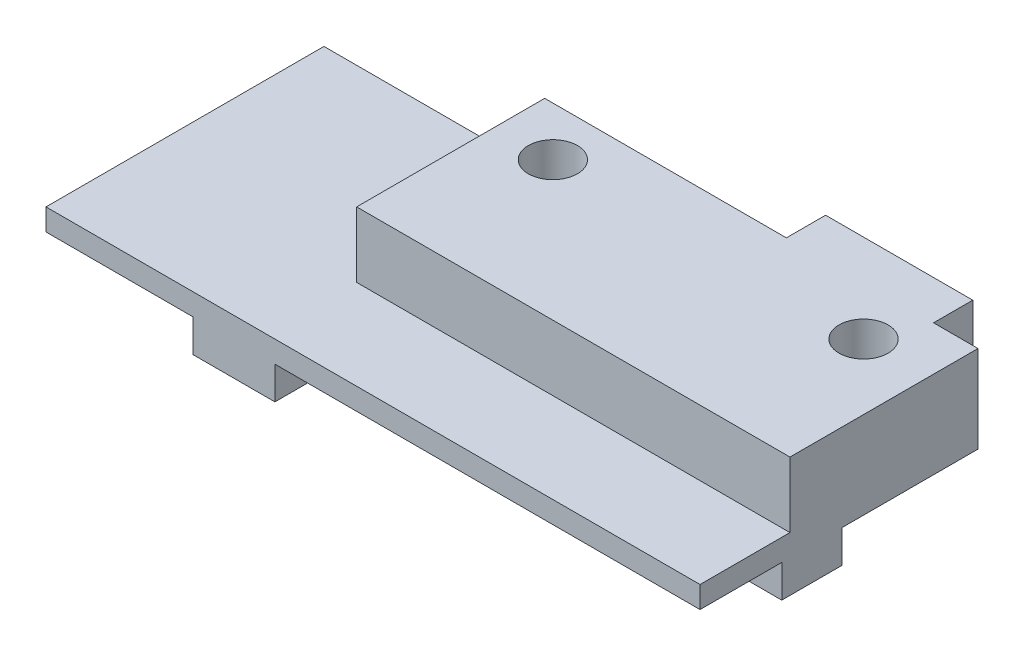
SolidWorks part; units mm, degrees
ref_plane "Спереди" through (0, 0, 0) normal (0, 0, 1) x (1, 0, 0)
ref_plane "Сверху" through (0, 0, 0) normal (0, 1, 0) x (1, 0, 0)
ref_plane "Справа" through (0, 0, 0) normal (1, 0, 0) x (0, 0, -1)
sketch "Эскиз1" plane through (0, 0, 0) normal (0, 1, 0) x (1, 0, 0)
  line L1 (-20, 8.5) -> (20, 8.5)
  line L2 (-20, 8.5) -> (-20, -8.5)
  line L3 (-20, -8.5) -> (20, -8.5)
  line L4 (20, 8.5) -> (20, -8.5)
  line L5 (-20, 8.5) -> (20, -8.5) construction
  line L6 (-20, -8.5) -> (20, 8.5) construction
  point P0 (0, 0)
  dimension "D1" = 17
  dimension "D2" = 40
extrude "Бобышка-Вытянуть1" add sketch "Эскиз1" along normal blind 1.33
sketch "Эскиз2" plane through (0, 1.33, 0) normal (0, 1, 0) x (1, 0, 0)
  line L1 (20, 8.5) -> (-6.5, 8.5)
  line L2 (20, 8.5) -> (20, -3)
  line L3 (20, -3) -> (-6.5, -3)
  line L4 (-6.5, 8.5) -> (-6.5, -3)
  line L5 (8.28, 8.5) -> (17.28, 8.5)
  line L6 (8.28, 8.5) -> (8.28, 10.9)
  line L7 (8.28, 10.9) -> (17.28, 10.9)
  line L8 (17.28, 8.5) -> (17.28, 10.9)
  line M1 (20, -8.5) -> (20, 8.5)
  line M2 (20, 8.5) -> (-20, 8.5)
  dimension "D1" = 2.4
  dimension "D2" = 11.5
  dimension "D3" = 26.5
  dimension "D4" = 9
  dimension "D5" = 2.72
extrude "Бобышка-Вытянуть2" add sketch "Эскиз2" along normal blind 4 contours L1 L4 L3 M2 M1 | L1 L8 L7 L6
sketch "Эскиз3" plane through (0, 0, 0) normal (0, -1, 0) x (1, 0, 0)
  line L0 (20, -8.5) -> (-20, -8.5) construction
  line L1 (-6, -8.5) -> (-11, -8.5)
  line L2 (-6, -8.5) -> (-6, 8.5)
  line L3 (-6, 8.5) -> (-11, 8.5)
  line L4 (-11, -8.5) -> (-11, 8.5)
  line L5 (-20, 8.5) -> (20, 8.5) construction
  line L6 (20, 8.5) -> (20, -8.5) construction
  line L7 (20, -0.19) -> (-6, -0.19)
  line L8 (20, -0.19) -> (20, 3.5)
  line L9 (20, 3.5) -> (-6, 3.5)
  line L10 (-6, -0.19) -> (-6, 3.5)
  line M2 (20, 8.5) -> (-20, 8.5)
  line M4 (-20, -8.5) -> (20, -8.5)
  dimension "D1" = 5
  dimension "D2" = 3.69
  dimension "D3" = 26
  dimension "D4" = 5
extrude "Бобышка-Вытянуть3" add sketch "Эскиз3" along normal blind 2 contours L4 L2 M4 M2 | L7 L10 L9 L8
sketch "Эскиз4" plane through (0, 0, 0) normal (0, -1, 0) x (1, 0, 0)
  line L0 (20, -0.19) -> (20, -8.5) construction
  line L1 (20, -8.5) -> (-6, -8.5) construction
  circle A0 centre (16, -5.5) radius 1.5
  circle A1 centre (-3, -5.5) radius 1.5
  dimension "D1" = 3
  dimension "D2" = 4
  dimension "D3" = 23
  dimension "D4" = 3
  dimension "D5" = 3
extrude "Вырез-Вытянуть1" cut sketch "Эскиз4" against normal through all
